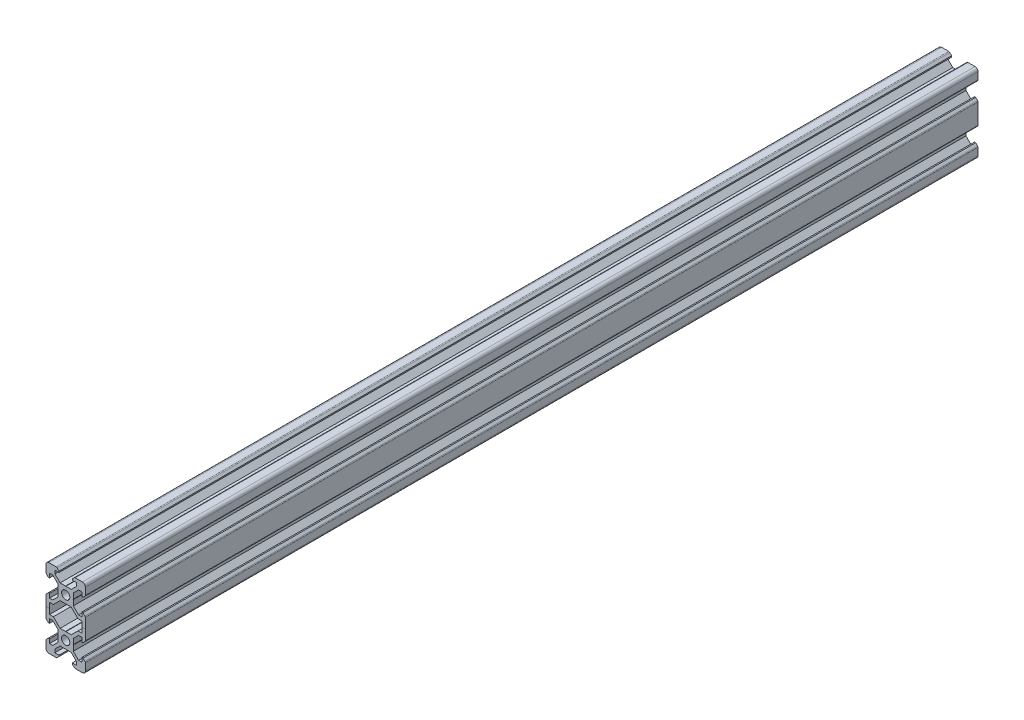
SolidWorks part; units mm, degrees
material "6063-T5"
ref_plane "Front" through (0, 0, 0) normal (0, 0, 1) x (1, 0, 0)
ref_plane "Top" through (0, 0, 0) normal (0, 1, 0) x (1, 0, 0)
ref_plane "Right" through (0, 0, 0) normal (1, 0, 0) x (0, 0, -1)
sketch "Sketch1" plane through (0, 0, 0) normal (0, 0, 1) x (1, 0, 0)
  line L0 (-8.5, 10) -> (-10, 8.5) construction
  line L1 (-8.5, 10) -> (-4.8628, 10)
  line L2 (-10, 8.5) -> (-10, 4.8628)
  line L4 (10, 8.5) -> (10, 4.8628)
  line L5 (-10, 10) -> (10, -10) construction
  line L6 (-10, -10) -> (10, 10) construction
  line L7 (8.2, -5.5) -> (8.2, -3.3865)
  line L8 (-8.2, -5.5) -> (-8.2, -3.3865)
  line L9 (-5.5, 8.2) -> (-3.3865, 8.2)
  line L10 (-8.2, -12.7) -> (-8.2, -7.3)
  line L11 (-3.9005, 2.8395) -> (-6.561, 5.5)
  line L12 (-6.561, 5.5) -> (-8.2, 5.5)
  line L13 (-2.8395, -3.9005) -> (-0.1, -3.9005)
  line L14 (-3.9005, -2.8395) -> (-3.9005, -0.1)
  line L15 (-2.8395, 3.9005) -> (-0.1, 3.9005)
  line L16 (3.9005, -2.8395) -> (3.9005, -0.1)
  line L17 (-8.2, 3.3865) -> (-8.81, 3.3865)
  line L18 (-8.81, 3.3865) -> (-9.7976, 4.3741)
  line L19 (8.5, 10) -> (10, 8.5) construction
  line L20 (-2.8395, 3.9005) -> (-5.5, 6.561)
  line L21 (-5.5, 6.561) -> (-5.5, 8.2)
  line L22 (-3.3865, 8.2) -> (-3.3865, 8.81)
  line L23 (-3.3865, 8.81) -> (-4.3741, 9.7976)
  line L24 (0, 24.069) -> (0, -33.8154) construction
  line L25 (3.3865, 8.81) -> (4.3741, 9.7976)
  line L26 (3.3865, 8.2) -> (3.3865, 8.81)
  line L27 (5.5, 6.561) -> (5.5, 8.2)
  line L28 (2.8395, 3.9005) -> (5.5, 6.561)
  line L29 (3.3865, 8.2) -> (5.5, 8.2)
  line L30 (4.8628, 10) -> (8.5, 10)
  line L31 (-0.1, 3.9005) -> (0, 3.8005)
  line L32 (0.1, 3.9005) -> (0, 3.8005)
  line L33 (0.1, 3.9005) -> (2.8395, 3.9005)
  line L34 (25.9287, 0) -> (-28.3459, 0) construction
  line L35 (-0.1, -3.9005) -> (0, -3.8005)
  line L36 (0.1, -3.9005) -> (0, -3.8005)
  line L37 (0.1, -3.9005) -> (2.8395, -3.9005)
  line L38 (-3.9005, 0.1) -> (-3.8005, 0)
  line L39 (-3.8005, 0) -> (-3.9005, -0.1)
  line L40 (-3.9005, 0.1) -> (-3.9005, 2.8395)
  line L41 (3.9005, 0.1) -> (3.8005, 0)
  line L42 (3.8005, 0) -> (3.9005, -0.1)
  line L43 (3.9005, 0.1) -> (3.9005, 2.8395)
  line L44 (8.81, 3.3865) -> (9.7976, 4.3741)
  line L45 (8.2, 3.3865) -> (8.81, 3.3865)
  line L46 (6.561, 5.5) -> (8.2, 5.5)
  line L47 (3.9005, 2.8395) -> (6.561, 5.5)
  line L48 (2.8395, -3.9005) -> (5.5, -6.561)
  line L49 (3.9005, -2.8395) -> (6.561, -5.5)
  line L50 (-2.8395, -3.9005) -> (-5.5, -6.561)
  line L51 (-3.9005, -2.8395) -> (-6.561, -5.5)
  line L52 (6.561, -5.5) -> (8.2, -5.5)
  line L53 (-6.561, -5.5) -> (-8.2, -5.5)
  line L54 (-8.81, -3.3865) -> (-9.7976, -4.3741)
  line L55 (-8.2, -3.3865) -> (-8.81, -3.3865)
  line L56 (8.81, -3.3865) -> (9.7976, -4.3741)
  line L57 (8.2, -3.3865) -> (8.81, -3.3865)
  line L58 (8.2, 3.3865) -> (8.2, 5.5)
  line L59 (10, -4.8628) -> (10, -15.1372)
  line L60 (-8.2, 3.3865) -> (-8.2, 5.5)
  line L61 (-10, -4.8628) -> (-10, -15.1372)
  line L62 (-28.3459, -10) -> (-10, -10) construction
  line L63 (-3.9005, -20.1) -> (-3.9005, -22.8395)
  line L64 (-3.9005, -20.1) -> (-3.8005, -20)
  line L65 (-3.8005, -20) -> (-3.9005, -19.9)
  line L66 (3.9005, -20.1) -> (3.9005, -22.8395)
  line L67 (3.9005, -20.1) -> (3.8005, -20)
  line L68 (3.8005, -20) -> (3.9005, -19.9)
  line L69 (6.561, -14.5) -> (8.2, -14.5)
  line L70 (3.9005, -17.1605) -> (6.561, -14.5)
  line L71 (3.9005, -17.1605) -> (3.9005, -19.9)
  line L72 (-3.9005, -17.1605) -> (-3.9005, -19.9)
  line L73 (-3.9005, -17.1605) -> (-6.561, -14.5)
  line L74 (-6.561, -14.5) -> (-8.2, -14.5)
  line L75 (-8.2, -16.6135) -> (-8.81, -16.6135)
  line L76 (-8.81, -16.6135) -> (-9.7976, -15.6259)
  line L77 (8.2, -16.6135) -> (8.81, -16.6135)
  line L78 (8.81, -16.6135) -> (9.7976, -15.6259)
  line L79 (-2.8395, -16.0995) -> (-5.5, -13.439)
  line L80 (-2.8395, -16.0995) -> (-0.1, -16.0995)
  line L81 (-0.1, -16.0995) -> (0, -16.1995)
  line L82 (0.1, -16.0995) -> (0, -16.1995)
  line L83 (0.1, -16.0995) -> (2.8395, -16.0995)
  line L84 (2.8395, -16.0995) -> (5.5, -13.439)
  line L85 (-8.2, -16.6135) -> (-8.2, -14.5)
  line L86 (8.2, -16.6135) -> (8.2, -14.5)
  line L87 (2.8395, -23.9005) -> (5.5, -26.561)
  line L88 (-2.8395, -23.9005) -> (-5.5, -26.561)
  line L89 (-0.1, -23.9005) -> (0, -23.8005)
  line L90 (0.1, -23.9005) -> (0, -23.8005)
  line L91 (0.1, -23.9005) -> (2.8395, -23.9005)
  line L92 (-2.8395, -23.9005) -> (-0.1, -23.9005)
  line L93 (-10, -28.5) -> (-10, -24.8628)
  line L94 (10, -28.5) -> (10, -24.8628)
  line L95 (8.81, -23.3865) -> (9.7976, -24.3741)
  line L96 (-8.81, -23.3865) -> (-9.7976, -24.3741)
  line L97 (-8.2, -23.3865) -> (-8.81, -23.3865)
  line L98 (8.2, -23.3865) -> (8.81, -23.3865)
  line L99 (8.2, -23.3865) -> (8.2, -25.5)
  line L100 (-8.2, -23.3865) -> (-8.2, -25.5)
  line L101 (-6.561, -25.5) -> (-8.2, -25.5)
  line L102 (6.561, -25.5) -> (8.2, -25.5)
  line L103 (3.9005, -22.8395) -> (6.561, -25.5)
  line L104 (-3.9005, -22.8395) -> (-6.561, -25.5)
  line L105 (-5.5, -28.2) -> (-3.3865, -28.2)
  line L106 (3.3865, -28.2) -> (5.5, -28.2)
  line L107 (3.3865, -28.2) -> (3.3865, -28.81)
  line L108 (3.3865, -28.81) -> (4.3741, -29.7976)
  line L109 (-3.3865, -28.2) -> (-3.3865, -28.81)
  line L110 (-3.3865, -28.81) -> (-4.3741, -29.7976)
  line L111 (-8.5, -30) -> (-4.8628, -30)
  line L112 (4.8628, -30) -> (8.5, -30)
  line L113 (-5.5, -26.561) -> (-5.5, -28.2)
  line L114 (5.5, -26.561) -> (5.5, -28.2)
  line L115 (-6.239, -7.3) -> (-8.2, -7.3)
  line L116 (-5.5, -6.561) -> (-6.239, -7.3)
  line L117 (6.239, -7.3) -> (8.2, -7.3)
  line L118 (5.5, -6.561) -> (6.239, -7.3)
  line L119 (-6.239, -12.7) -> (-8.2, -12.7)
  line L120 (-5.5, -13.439) -> (-6.239, -12.7)
  line L121 (5.5, -13.439) -> (6.239, -12.7)
  line L122 (6.239, -12.7) -> (8.2, -12.7)
  line L123 (8.2, -12.7) -> (8.2, -7.3)
  line L125 (10, -10) -> (25.9287, -10) construction
  circle A0 centre (0, 0) radius 2.1
  arc A1 (-8.5, 10) -> (-10, 8.5) centre (-8.5, 8.5) ccw
  arc A2 (10, 8.5) -> (8.5, 10) centre (8.5, 8.5) ccw
  arc A3 (-4.3741, 9.7976) -> (-4.8628, 10) centre (-4.8628, 9.3088) ccw
  arc A4 (4.8628, 10) -> (4.3741, 9.7976) centre (4.8628, 9.3088) ccw
  circle A5 centre (0, -20) radius 2.1
  arc A6 (9.7976, 4.3741) -> (10, 4.8628) centre (9.3088, 4.8628) ccw
  arc A7 (-10, 4.8628) -> (-9.7976, 4.3741) centre (-9.3088, 4.8628) ccw
  arc A8 (-10, -4.8628) -> (-9.7976, -4.3741) centre (-9.3088, -4.8628) cw
  arc A9 (9.7976, -4.3741) -> (10, -4.8628) centre (9.3088, -4.8628) cw
  arc A10 (-10, -15.1372) -> (-9.7976, -15.6259) centre (-9.3088, -15.1372) ccw
  arc A11 (9.7976, -15.6259) -> (10, -15.1372) centre (9.3088, -15.1372) ccw
  arc A12 (-10, -24.8628) -> (-9.7976, -24.3741) centre (-9.3088, -24.8628) cw
  arc A13 (9.7976, -24.3741) -> (10, -24.8628) centre (9.3088, -24.8628) cw
  arc A14 (4.8628, -30) -> (4.3741, -29.7976) centre (4.8628, -29.3088) cw
  arc A15 (-4.3741, -29.7976) -> (-4.8628, -30) centre (-4.8628, -29.3088) cw
  arc A16 (-8.5, -30) -> (-10, -28.5) centre (-8.5, -28.5) cw
  arc A17 (10, -28.5) -> (8.5, -30) centre (8.5, -28.5) cw
  point P17 (-9.25, 9.25)
  point P21 (9.25, 9.25)
  dimension "D2" = 4.2
  dimension "D4" = 1.5
  dimension "D3" = 20
  dimension "D5" = 0.529
  dimension "D6" = 6.773
  dimension "D7" = 90
  dimension "D8" = 11
  dimension "D9" = 0.61
  dimension "D10" = 0.1
  dimension "D11" = 0.1
  dimension "D12" = 0.1
  dimension "D13" = 0.1
  dimension "D14" = 5.679
  dimension "D15" = 1.639
  dimension "D16" = 1.8
  dimension "D17" = 90
  dimension "D18" = 6.773
  dimension "D19" = 90
  dimension "D20" = 20
  dimension "D21" = 1.8
extrude "Boss-Extrude2" add sketch "Sketch1" along normal blind 454
sketch "Sketch2" plane through (0, 0, 0) normal (0, 0, -1) x (-1, 0, 0)
  line L0 (-10, -10) -> (10, -10)
  line L1 (-10, -15.1372) -> (-10, -4.8628) construction
  line L2 (10, -4.8628) -> (10, -15.1372) construction
split line "SideFixture1 - SplitLine"
sketch "Sketch3" plane through (0, 0, 454) normal (0, 0, 1) x (1, 0, 0)
  line L0 (-10, -10) -> (10, -10)
  line L1 (-10, -4.8628) -> (-10, -15.1372) construction
  line L2 (10, -15.1372) -> (10, -4.8628) construction
split line "SideFixture2 - SplitLine"
sketch "Sketch4" plane through (0, 10, 0) normal (0, 1, 0) x (1, 0, 0)
  line L0 (-8.5, -227) -> (8.5, -227)
  line L1 (-8.5, -454) -> (-8.5, 0) construction
  line L2 (8.5, -454) -> (8.5, 0) construction
split line "SideFixture3 - SplitLine"
